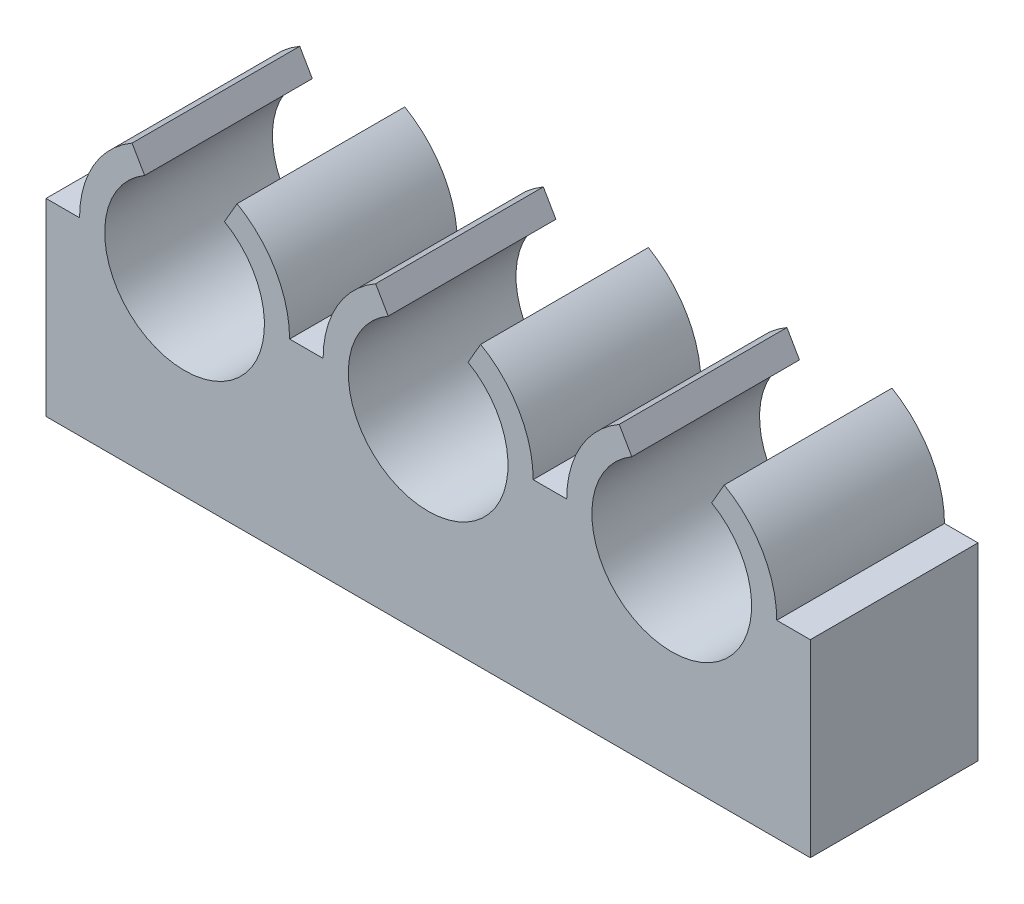
SolidWorks part; units mm, degrees
ref_plane "Front Plane" through (0, 0, 0) normal (0, 0, 1) x (1, 0, 0)
ref_plane "Top Plane" through (0, 0, 0) normal (0, 1, 0) x (1, 0, 0)
ref_plane "Right Plane" through (0, 0, 0) normal (1, 0, 0) x (0, 0, -1)
sketch "Sketch4" plane through (0, 0, 0) normal (0, 0, 1) x (1, 0, 0)
  line L0 (-20.7875, 0) -> (-20.7875, -11.2625)
  line L1 (-20.7875, -11.2625) -> (20.7875, -11.2625)
  line L2 (20.7875, -11.2625) -> (20.7875, 0)
  line L3 (-8.2625, 0) -> (-6.2625, 0)
  line L4 (6.2625, 0) -> (8.2625, 0)
  line L5 (-17.6563, 5.4235) -> (-14.525, 0)
  line L6 (-14.525, 0) -> (-11.3938, 5.4235)
  line L7 (-3.1313, 5.4235) -> (0, 0)
  line L8 (0, 0) -> (3.1312, 5.4235)
  line L9 (11.3937, 5.4235) -> (14.525, 0)
  line L10 (14.525, 0) -> (17.6562, 5.4235)
  line L11 (-14.525, 6.2625) -> (-14.525, 0) construction
  line L12 (0, 6.2625) -> (0, 0) construction
  line L13 (14.525, 6.2625) -> (14.525, 0) construction
  line L14 (20.7875, 0) -> (22.7875, 0)
  line L15 (22.7875, 0) -> (22.7875, -11.2625)
  line L16 (22.7875, -11.2625) -> (20.7875, -11.2625)
  line L17 (-20.7875, 0) -> (-22.7875, 0)
  line L18 (-22.7875, 0) -> (-22.7875, -11.2625)
  line L19 (-22.7875, -11.2625) -> (-20.7875, -11.2625)
  circle A0 centre (-14.525, 0) radius 4.7625
  circle A1 centre (0, 0) radius 4.7625
  circle A2 centre (14.525, 0) radius 4.7625
  circle A3 centre (-14.525, 0) radius 6.2625
  circle A4 centre (0, 0) radius 6.2625
  circle A5 centre (14.525, 0) radius 6.2625
  dimension "D1" = 9.525
  dimension "D4" = 12.525
  dimension "D2" = 14.525
  dimension "D3" = 14.525
  dimension "D5" = 11.2625
  dimension "D6" = 60
  dimension "D7" = 30
  dimension "D8" = 60
  dimension "D9" = 30
  dimension "D10" = 60
  dimension "D11" = 30
  dimension "D12" = 2
extrude "Boss-Extrude1" add sketch "Sketch4" along normal blind 10 contours A5 L4 A4 L3 A3 L0 L1 L2 | A3 L6 A0 L5 | A4 L8 A1 L7 | A5 L10 A2 L9 | L18 L19 L0 L17 | L16 L15 L14 L2
equation "\"D2@Sketch4\"=\"D1@Sketch4\"+5"
equation "\"D3@Sketch4\"=\"D2@Sketch4\""
equation "\"D4@Sketch4\"=\"D1@Sketch4\"+3"
equation "\"D5@Sketch4\"=(\"D4@Sketch4\"/2)+5"
